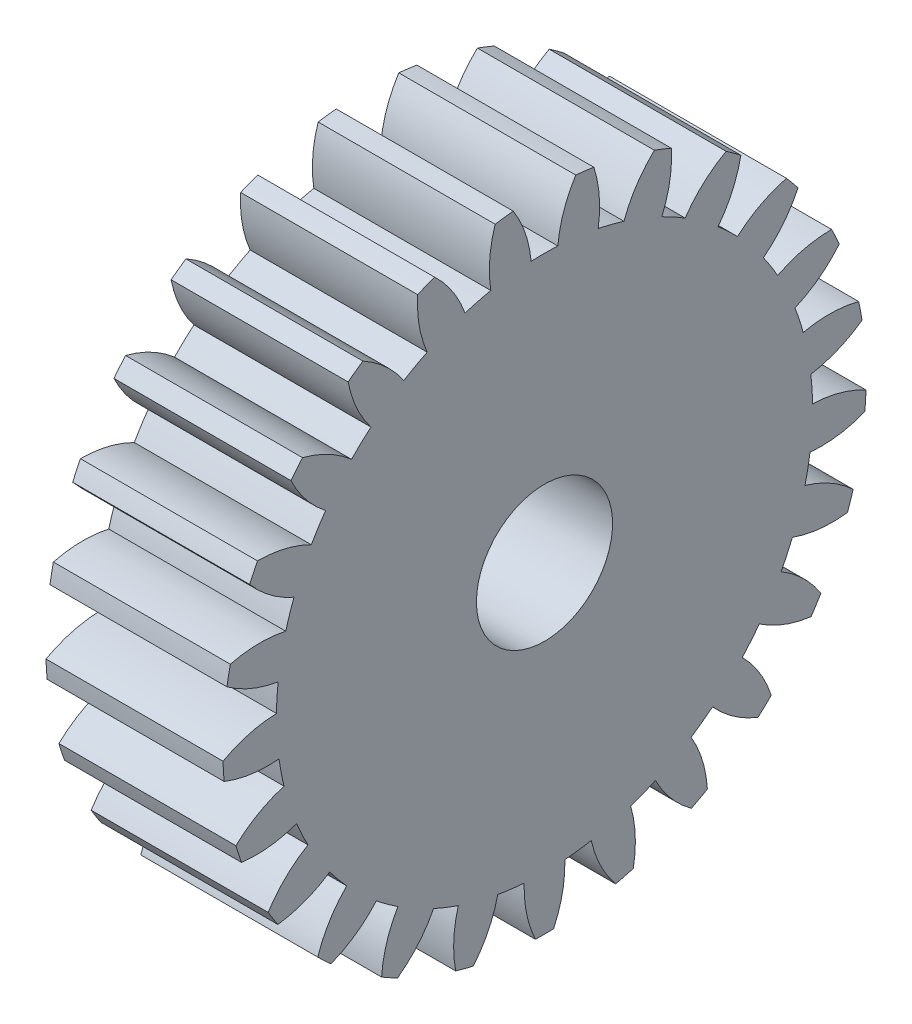
SolidWorks part; units mm, degrees
ref_plane "Plane1" through (0, 0, 0) normal (0, 0, 1) x (1, 0, 0)
ref_plane "Plane2" through (0, 0, 0) normal (0, 1, 0) x (1, 0, 0)
ref_plane "Plane3" through (0, 0, 0) normal (1, 0, 0) x (0, 0, -1)
other "Configuration Table"
sketch "HoldingSke" plane through (0, 0, 0) normal (0, 1, 0) x (1, 0, 0)
  line L0 (0, 0) -> (0.5179, -0.2415)
  line L1 (-15, 0) -> (100, 0) construction
  line L2 (0, 0) -> (-2.1039, 2.3779)
  line L3 (0, 0) -> (-11.863, 4.5341)
  line L4 (0, 0) -> (7.8269, 3.6497)
  line L5 (0, 0) -> (-46.8476, -17.4728)
  line L6 (0, 0) -> (-10.7765, -7.2709)
  line L7 (-2.1039, 2.3779) -> (8.6586, 51.2059)
  line L8 (-76.2, 54.61) -> (-74.4, 54.61)
  line L9 (-67.7845, 28.3722) -> (-49.3413, 33.142)
  line L10 (-76.2, 71.12) -> (104.1128, 71.12)
  line L11 (0, 0) -> (-13, 0)
  line L12 (-76.2, 101.6) -> (-76.147, 101.6)
  line L13 (24.9733, 27.94) -> (52.9518, 28.4284)
  line L14 (24.9733, 27.94) -> (24.9743, 27.94)
  line L15 (24.9733, 27.94) -> (100.4006, 29.5858)
  line L16 (-63.627, -1.75) -> (-12.827, -1.75)
  circle A0 centre (0, 0) radius 5
  circle A1 centre (0, 0) radius 19.6865
  circle A2 centre (0, 0) radius 37.5
  circle A3 centre (0, 0) radius 5
  dimension "MHD" = 39.373
  dimension "Hub_dia" = 75
  dimension "Bore" = 10
  dimension "MBD" = 10
  dimension "Num_teeth" = 25
  dimension "Pitch" = 0.5714
  dimension "Overall_len" = 50
  dimension "Show_teeth" = 25
  dimension "Thickness" = 13
  dimension "OAL" = 50.0001
  dimension "T_dim" = 1.8
  dimension "Ap" = 14.5
  dimension "H" = 19.05
  dimension "Pitch_radius" = 180.3128
  dimension "Width" = 13
  dimension "Backlash" = 0.053
  dimension "Addendum_fac" = 1
  dimension "Dedendum_fac" = 1.25
  dimension "Clearance_fac" = 0.25
  dimension "Dedendum_add" = 0.001
  dimension "Module" = 1.75
sketch "BasProSke" plane through (0, 0, 0) normal (0, 1, 0) x (1, 0, 0)
  line L0 (-10, 0) -> (60, 0) construction
  line L1 (0, 0) -> (0, 23.625)
  line L2 (0, 0) -> (13, 0)
  line L3 (13, 0) -> (13, 23.625)
  line L4 (13, 23.625) -> (0, 23.625)
  dimension "Thickness" = 13
  dimension "Diameter" = 47.25
revolve "Base-Revolve" add sketch "BasProSke" angle 360 about L0
sketch "TooCutSke" plane through (0, 0, 0) normal (1, 0, 0) x (0, 0, -1)
  line L1 (0, 0) -> (0, 107) construction
  line L2 (0, 0) -> (-1.4663, 21.8258) construction
  line L3 (0, 0) -> (-5.4739, 43.3306) construction
  line L4 (-1.4663, 21.8258) -> (-2.737, 21.6653) construction
  arc A0 (0.9777, 19.6622) -> (-0.9777, 19.6622) centre (0, 0) ccw
  arc A1 (2.3109, 23.5372) -> (-2.3109, 23.5372) centre (0, 0) ccw
  circle A2 centre (0, 0) radius 21.875 construction
  circle A3 centre (0, 0) radius 21.1782 construction
  arc A4 (-0.9777, 19.6622) -> (-2.3109, 23.5372) centre (-9.6883, 18.8323) ccw
  arc A5 (2.3109, 23.5372) -> (0.9777, 19.6622) centre (9.6883, 18.8323) ccw
  dimension "Root_dia" = 39.373
  dimension "Overcut_dia" = 47.3008
  dimension "Pitch_dia" = 43.75
  dimension "Base_dia" = 42.3565
  dimension "Flank_rad" = 8.75
  dimension "Half_ang" = 7.2
  dimension "Half_CT" = 1.2808
extrude "ToothCut" cut sketch "TooCutSke" along normal through all
fillet "Breaks" [suppressed] radius 0.035
fillet "RootFillets" [suppressed] radius 0.4385
pattern_circular "TeethCuts" count 25 every 14.4 about axis through (-10, 0, 0) along (1, 0, 0) of "ToothCut", "RootFillets", "Breaks"
sketch "HubNeaOneSke" plane through (0, 0, 0) normal (-1, 0, 0) x (0, 0, 1)
  circle A0 centre (0, 0) radius 19.6865
  dimension "Diameter" = 39.373
extrude "HubNearOne" [suppressed] add sketch "HubNeaOneSke" along normal blind 37.0001
sketch "HubNeaBotSke" plane through (0, 0, 0) normal (-1, 0, 0) x (0, 0, 1)
  circle A0 centre (0, 0) radius 19.6865
  dimension "Diameter" = 39.373
extrude "HubNearBoth" [suppressed] add sketch "HubNeaBotSke" along normal blind 18.5
ref_plane "FarPln" through (13, 0, 0) normal (1, 0, 0) x (0, 0, -1)
sketch "HubFarSke" plane through (13, 0, 0) normal (1, 0, 0) x (0, 0, -1)
  circle A0 centre (0, 0) radius 19.6865
  dimension "Diameter" = 39.373
extrude "HubFar" [suppressed] add sketch "HubFarSke" along normal blind 18.5
sketch "BorSke" plane through (0, 0, 0) normal (1, 0, 0) x (0, 0, -1)
  circle A0 centre (0, 0) radius 5
  dimension "Diameter" = 10
extrude "Bore" cut sketch "BorSke" along normal mid plane 100.0001
sketch "KeySke" plane through (0, 0, 0) normal (1, 0, 0) x (0, 0, -1)
  line L0 (-2, 0) -> (-2, 6.8)
  line L1 (-2, 6.8) -> (2, 6.8)
  line L2 (2, 6.8) -> (2, 0)
  line L3 (0, 0) -> (0, 34) construction
  line L4 (-2, 0) -> (2, 0)
  dimension "Offset" = 6.8
  dimension "Width" = 4
extrude "Keyway" [suppressed] cut sketch "KeySke" along normal mid plane 100.0001
pattern_circular "Keyway2" [suppressed] count 2 every 90 about axis through (-10, 0, 0) along (1, 0, 0)
equation "' \"Module@HoldingSke\" = 6.35"
equation "' \"Num_teeth@HoldingSke\" = 12"
equation "' \"Ap@HoldingSke\" =  20"
equation "' \"Ap@HoldingSke\" = 20"
equation "' \"Width@HoldingSke\" = 0.5 * 25.4"
equation "' \"Hub_dia@HoldingSke\"= 1 * 25.4"
equation "' \"Hub_dia@HoldingSke\" = 1 * 25.4"
equation "' \"Overall_len@HoldingSke\" = 1.0 * 25.4"
equation "' \"Bore@HoldingSke\" = 0.75 * 25.4"
equation "' \"T_dim@HoldingSke\" = 0.1 * 25.4"
equation "' \"Width@KeySke\" = 0.25 * 25.4"
equation "' \"Show_teeth@HoldingSke\" = 13"
equation "' \"Backlash@HoldingSke\" = 0.009 * 25.4"
equation "' \"Addendum_fac@HoldingSke\" = 1.0"
equation "' \"Dedendum_fac@HoldingSke\" = 1.25"
equation "' \"Dedendum_add@HoldingSke\" = 0.00005 * 25.4"
equation "' \"Clearance_fac@HoldingSke\" = 0.25"
equation "\"Pitch@HoldingSke\" = 1 / \"Module@HoldingSke\""
equation "\"Overcut_dia@TooCutSke\" = (\"Num_teeth@HoldingSke\" + 2 * \"Addendum_fac@HoldingSke\") / \"Pitch@HoldingSke\" + 0.002 * 25.4"
equation "\"Pitch_dia@TooCutSke\" = \"Num_teeth@HoldingSke\" / \"Pitch@HoldingSke\""
equation "\"Base_dia@TooCutSke\" = \"Num_teeth@HoldingSke\" / \"Pitch@HoldingSke\" * cos((\"Ap@HoldingSke\"  * 3.14159265 / 180))"
equation "\"Root_dia@TooCutSke\" = (\"Num_teeth@HoldingSke\" + 2) / \"Pitch@HoldingSke\" - 2 * (\"Addendum_fac@HoldingSke\" + \"Dedendum_fac@HoldingSke\") / \"Pitch@HoldingSke\" - \"Dedendum_add@HoldingSke\" * 2"
equation "\"Half_ang@TooCutSke\" = 180 / \"Num_teeth@HoldingSke\""
equation "\"Half_CT@TooCutSke\" = \"Num_teeth@HoldingSke\" / \"Pitch@HoldingSke\" * sin((3.14159265 / 2 / \"Num_teeth@HoldingSke\")) / 2 - 7 * \"Backlash@HoldingSke\" / 4"
equation "\"Flank_rad@TooCutSke\" = \"Num_teeth@HoldingSke\" / \"Pitch@HoldingSke\" / 5"
equation "\"Radius@RootFillets\" = \"Clearance_fac@HoldingSke\" / \"Pitch@HoldingSke\" + \"Dedendum_add@HoldingSke\""
equation "\"Break_rad@Breaks\" = 0.02 / \"Pitch@HoldingSke\""
equation "\"Thickness@HoldingSke\" = \"Width@HoldingSke\""
equation "\"OAL@HoldingSke\" = \"Thickness@HoldingSke\""
equation "\"MHD@HoldingSke\" = (\"Num_teeth@HoldingSke\" + 2) / \"Pitch@HoldingSke\" - 2 * (\"Addendum_fac@HoldingSke\" + \"Dedendum_fac@HoldingSke\")  / \"Pitch@HoldingSke\" - \"Dedendum_add@HoldingSke\" * 2"
equation "\"MBD@HoldingSke\" = (\"Num_teeth@HoldingSke\" + 2) / \"Pitch@HoldingSke\" - 2 * (\"Addendum_fac@HoldingSke\" + \"Dedendum_fac@HoldingSke\")  / \"Pitch@HoldingSke\" - \"Dedendum_add@HoldingSke\" * 2 - 0.002 * 25.4"
equation "\"MHD@HoldingSke\" = ((sgn( \"MHD@HoldingSke\" - \"Hub_dia@HoldingSke\" )-1)*( \"MHD@HoldingSke\" - \"Hub_dia@HoldingSke\" ))/-2+ \"Hub_dia@HoldingSke\""
equation "\"MBD@HoldingSke\" = ((sgn( \"MBD@HoldingSke\" - \"Bore@HoldingSke\" )-1)*( \"MBD@HoldingSke\" - \"Bore@HoldingSke\" ))/-2+ \"Bore@HoldingSke\""
equation "\"OAL@HoldingSke\" = ((sgn( \"OAL@HoldingSke\" - \"Overall_len@HoldingSke\" )+1)*( \"OAL@HoldingSke\" - \"Overall_len@HoldingSke\" ))/2 + \"Overall_len@HoldingSke\" + 0.000002 * 25.4"
equation "\"Num_teeth@TeethCuts\" = int( \"Show_teeth@HoldingSke\" ) + 1"
equation "\"Num_teeth@TeethCuts\" = ((sgn( \"Num_teeth@TeethCuts\" - \"Num_teeth@HoldingSke\" )-1)*( \"Num_teeth@TeethCuts\" - \"Num_teeth@HoldingSke\" ))/-2+ \"Num_teeth@HoldingSke\""
equation "\"Num_teeth@TeethCuts\" = ((sgn( \"Num_teeth@TeethCuts\" - 2.0)+1)*( \"Num_teeth@TeethCuts\" - 2.0))/2 +2.0"
equation "\"Angle@TeethCuts\" = 360.0 / \"Num_teeth@HoldingSke\""
equation "\"Diameter@BasProSke\" = (\"Num_teeth@HoldingSke\" + 2 * \"Addendum_fac@HoldingSke\") / \"Pitch@HoldingSke\""
equation "\"Thickness@BasProSke\"  = \"Thickness@HoldingSke\""
equation "' \"Fillet_rad@BasProSke\" =  \"Thickness@HoldingSke\" * 0.05"
equation "' \"Fillet_rad@BasProSke\" = \"Thickness@HoldingSke\" * 0.05"
equation "\"MHD@HoldingSke\" = ((sgn( \"MHD@HoldingSke\" - \"Root_dia@TooCutSke\" )-1)*( \"MHD@HoldingSke\" - \"Root_dia@TooCutSke\" ))/-2+ \"Root_dia@TooCutSke\""
equation "\"Diameter@HubNeaOneSke\" = \"MHD@HoldingSke\""
equation "\"Length@HubNearOne\" = \"OAL@HoldingSke\" - \"Thickness@BasProSke\""
equation "\"Diameter@HubNeaBotSke\" = \"MHD@HoldingSke\""
equation "\"Length@HubNearBoth\" = ( \"OAL@HoldingSke\" - \"Thickness@BasProSke\" ) / 2.0"
equation "\"Thickness@FarPln\" = \"Thickness@BasProSke\""
equation "\"Diameter@HubFarSke\" = \"MHD@HoldingSke\""
equation "\"Length@HubFar\" = ( \"OAL@HoldingSke\" - \"Thickness@BasProSke\" ) / 2.0"
equation "\"Diameter@BorSke\" = \"MBD@HoldingSke\""
equation "\"D1@Bore\" = \"OAL@HoldingSke\" * 2.0"
equation "\"D1@Keyway\" = \"OAL@HoldingSke\" * 2.0"
equation "\"Offset@KeySke\" = \"T_dim@HoldingSke\" + \"MBD@HoldingSke\" / 2.0"
